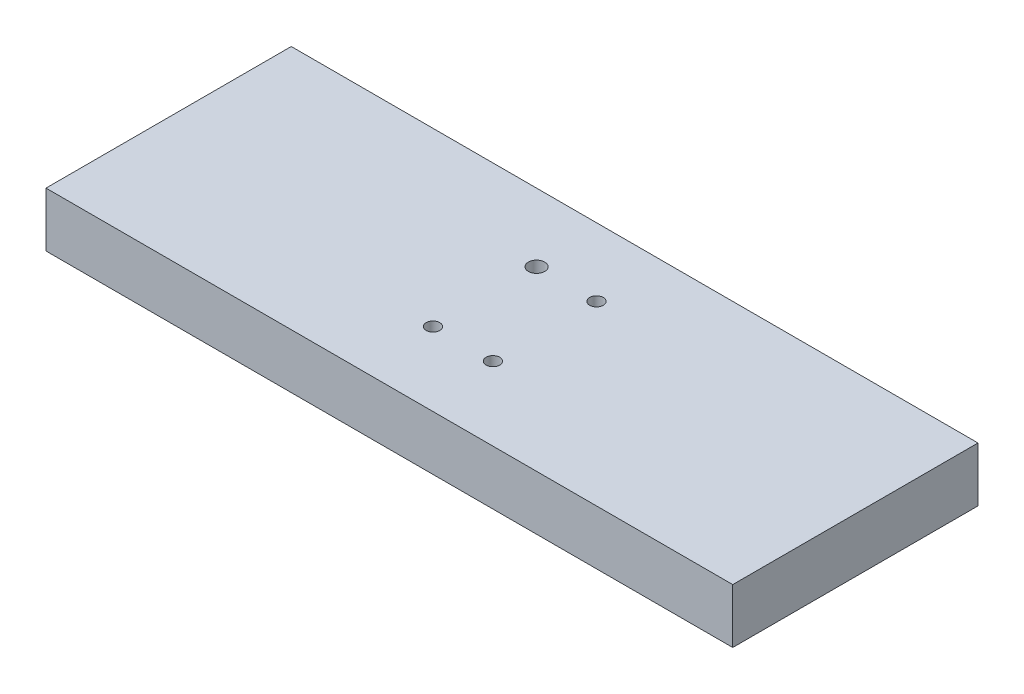
SolidWorks part; units mm, degrees
ref_plane "Piano frontale" through (0, 0, 0) normal (0, 0, 1) x (1, 0, 0)
ref_plane "Piano superiore" through (0, 0, 0) normal (0, 1, 0) x (1, 0, 0)
ref_plane "Piano destro" through (0, 0, 0) normal (1, 0, 0) x (0, 0, -1)
sketch "Schizzo1" plane through (0, 0, 0) normal (0, 1, 0) x (1, 0, 0)
  line L1 (126, -45) -> (-126, -45)
  line L2 (126, -45) -> (126, 45)
  line L3 (126, 45) -> (-126, 45)
  line L4 (-126, -45) -> (-126, 45)
  line L5 (126, -45) -> (-126, 45) construction
  line L6 (126, 45) -> (-126, -45) construction
  point P0 (0, 0)
  dimension "D1" = 90
  dimension "D2" = 252
extrude "Estrusione-Estrusione1" add sketch "Schizzo1" along normal blind 20
sketch "Schizzo2" plane through (0, 0, 0) normal (0, -1, 0) x (1, 0, 0)
  circle A0 centre (6, 20.5) radius 2.5 construction
  circle A1 centre (-16, 20.5) radius 2.5 construction
  circle A2 centre (6, 20.5) radius 2.5
  circle A3 centre (-16, 20.5) radius 2.5
  circle A4 centre (-16, -17.5) radius 2.5 construction
  circle A5 centre (6, -17.5) radius 2.5 construction
  circle A6 centre (-16, -17.5) radius 2.5
  circle A7 centre (6, -17.5) radius 2.5
  circle A8 centre (56, -17.5) radius 2.5
  circle A9 centre (106, -17.5) radius 2.5
  circle A10 centre (-56, -17.5) radius 2.5
  circle A11 centre (-96, -17.5) radius 2.5
  dimension "D1" = 3
  dimension "D2" = 3
sketch "Schizzo3" plane through (0, 20, 0) normal (0, 1, 0) x (1, 0, 0)
  circle A0 centre (-11, 20) radius 3 construction
  circle A1 centre (-11, 20) radius 3
  circle A2 centre (11, 20) radius 2.5 construction
  circle A3 centre (11, 20) radius 2.5
  circle A4 centre (11, -18) radius 2.5 construction
  circle A5 centre (-11, -18) radius 2.5 construction
  circle A6 centre (11, -18) radius 2.5
  circle A7 centre (-11, -18) radius 2.5
extrude "Taglio-Estrusione1" cut sketch "Schizzo3" against normal blind 20
